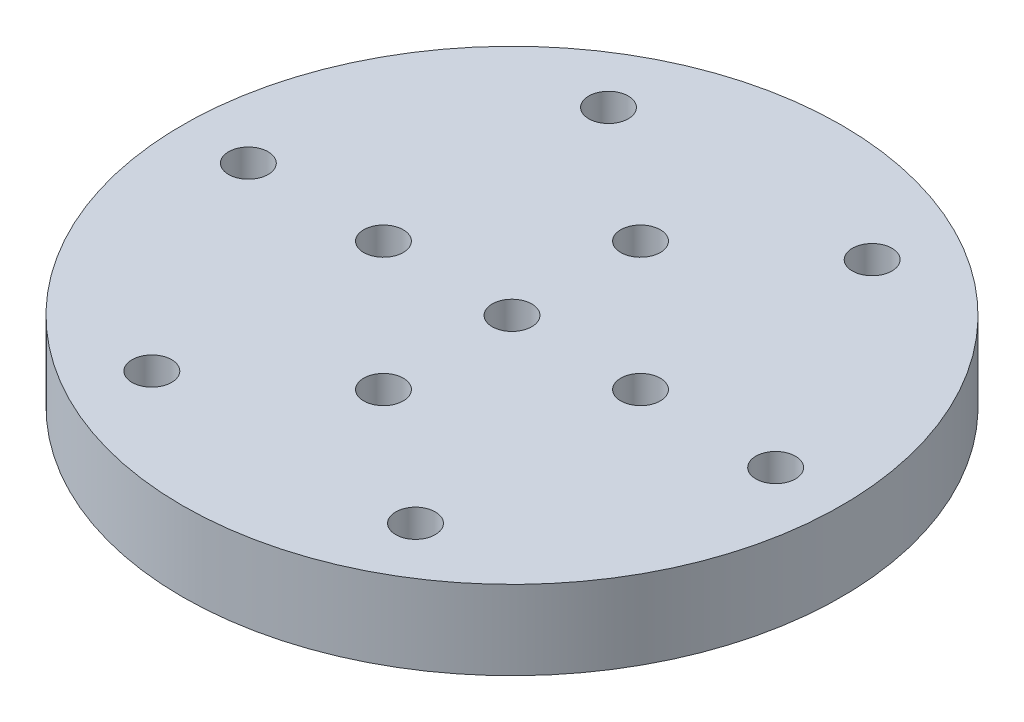
SolidWorks part; units mm, degrees
ref_plane "前视基准面" through (0, 0, 0) normal (0, 0, 1) x (1, 0, 0)
ref_plane "上视基准面" through (0, 0, 0) normal (0, 1, 0) x (1, 0, 0)
ref_plane "右视基准面" through (0, 0, 0) normal (1, 0, 0) x (0, 0, -1)
other "Configuration Table"
sketch "草图1" plane through (0, 0, 0) normal (0, 1, 0) x (1, 0, 0)
  circle A0 centre (0, 0) radius 25
  dimension "D1" = 50
extrude "凸台-拉伸1" add sketch "草图1" along normal blind 6
sketch "草图2" plane through (0, 6, 0) normal (0, 1, 0) x (1, 0, 0)
  circle A0 centre (0, 0) radius 9.75 construction
  circle A1 centre (9.75, 0) radius 1.5
  circle A2 centre (0, -9.75) radius 1.5
  circle A3 centre (-9.75, 0) radius 1.5
  circle A4 centre (0, 9.75) radius 1.5
  circle A5 centre (0, 0) radius 1.5
  circle A6 centre (0, 0) radius 20 construction
  circle A7 centre (-20, 0) radius 1.5
  circle A8 centre (-10, 17.3205) radius 1.5
  circle A9 centre (10, 17.3205) radius 1.5
  circle A10 centre (20, 0) radius 1.5
  circle A11 centre (10, -17.3205) radius 1.5
  circle A12 centre (-10, -17.3205) radius 1.5
  point P14 (0, 0)
  point P29 (0, 0)
  dimension "D1" = 19.5
  dimension "D2" = 4
  dimension "D3" = 3
  dimension "D4" = 3
  dimension "D5" = 40
  dimension "D6" = 3
  dimension "D7" = 6
extrude "切除-拉伸1" cut sketch "草图2" against normal blind 10
